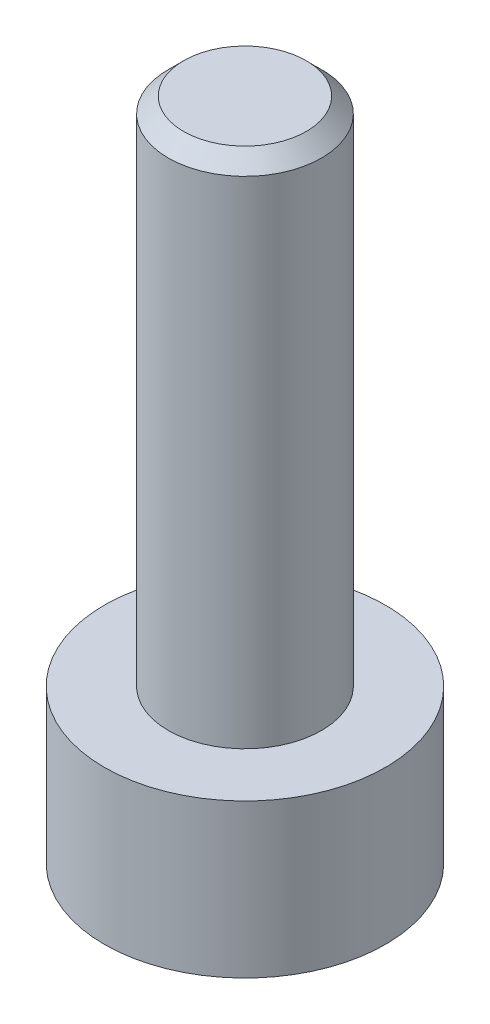
SolidWorks part; units mm, degrees
ref_plane "前视基准面" through (0, 0, 0) normal (0, 0, 1) x (1, 0, 0)
ref_plane "上视基准面" through (0, 0, 0) normal (0, 1, 0) x (1, 0, 0)
ref_plane "右视基准面" through (0, 0, 0) normal (1, 0, 0) x (0, 0, -1)
sketch "草图1" plane through (0, 0, 0) normal (0, 1, 0) x (1, 0, 0)
  circle A0 centre (0, 0) radius 2.75
  dimension "D1" = 5.5
extrude "凸台-拉伸1" add sketch "草图1" along normal blind 3
sketch "草图2" plane through (0, 3, 0) normal (0, 1, 0) x (1, 0, 0)
  circle A0 centre (0, 0) radius 1.5
  dimension "D1" = 3
sketch "草图3" plane through (0, 0, 0) normal (0, -1, 0) x (1, 0, 0)
  line L1 (0, 1.25) -> (-1.0825, 0.625)
  line L2 (-1.0825, 0.625) -> (-1.0825, -0.625)
  line L3 (-1.0825, -0.625) -> (0, -1.25)
  line L4 (0, -1.25) -> (1.0825, -0.625)
  line L5 (1.0825, -0.625) -> (1.0825, 0.625)
  line L6 (1.0825, 0.625) -> (0, 1.25)
  circle A0 centre (0, 0) radius 1.0825 construction
  dimension "D1" = 2.5
extrude "切除-拉伸1" cut sketch "草图3" against normal blind 1.5
extrude "凸台-拉伸2" add sketch "草图2" along normal blind 10
cosmetic thread "装饰螺纹线1" parameters "D1"=5, "D2"=2
chamfer "倒角1" distance 0.3 angle 45 1 edges at (0, 13, 1.5)
